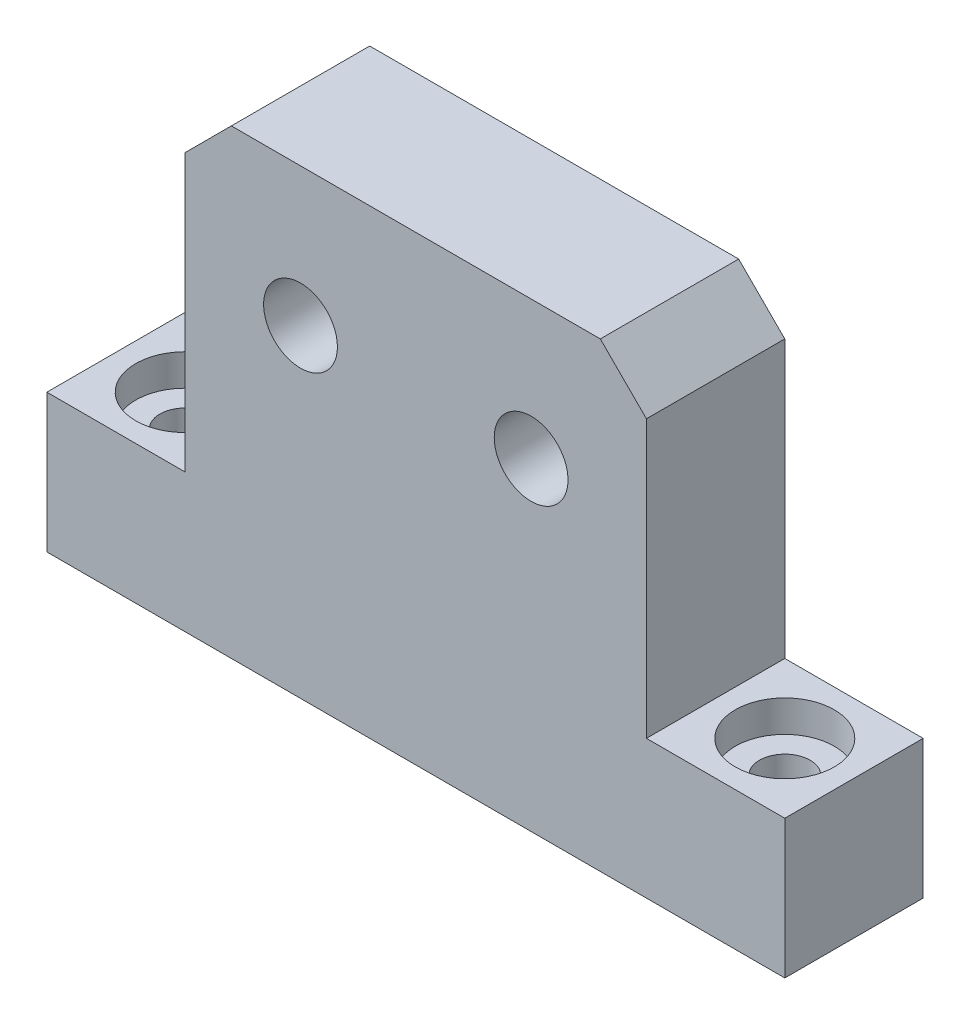
SolidWorks part; units mm, degrees
ref_plane "Front Plane" through (0, 0, 0) normal (0, 0, 1) x (1, 0, 0)
ref_plane "Top Plane" through (0, 0, 0) normal (0, 1, 0) x (1, 0, 0)
ref_plane "Right Plane" through (0, 0, 0) normal (1, 0, 0) x (0, 0, -1)
sketch "Sketch2" plane through (0, 0, 0) normal (0, 0, 1) x (1, 0, 0)
  line L0 (0, 0) -> (0, 100) construction
  line L1 (80, 0) -> (-80, 0)
  line L2 (-80, 0) -> (-80, 30)
  line L3 (-80, 30) -> (-50, 30)
  line L4 (-50, 30) -> (-50, 100)
  line L5 (-50, 100) -> (0, 100)
  line L6 (0, 70) -> (-50, 70) construction
  line L7 (-25, 100) -> (-25, 0) construction
  line L8 (25, 100) -> (25, 0) construction
  line L9 (0, 70) -> (50, 70) construction
  line L10 (50, 100) -> (0, 100)
  line L11 (50, 30) -> (50, 100)
  line L12 (80, 30) -> (50, 30)
  line L13 (80, 0) -> (80, 30)
  circle A0 centre (-25, 70) radius 8
  circle A1 centre (25, 70) radius 8
  circle A2 centre (-25, 70) radius 14 construction
  circle A3 centre (25, 70) radius 14 construction
  dimension "D5" = 16
  dimension "D7" = 28
  dimension "D1" = 100
  dimension "D2" = 80
  dimension "D3" = 30
  dimension "D4" = 30
  dimension "D6" = 70
extrude "Corpo - Furos 20mm" add sketch "Sketch2" along normal blind 30
chamfer "Chanfros 10x45°" distance 10 angle 45 2 edges at (-50, 100, 15) (50, 100, 15)
hole_wizard "Rebaixo Parafuso M10" positions "Sketch4" profile "Sketch5" counterbore size "M10" standard "ANSI Metric" end condition through all
sketch "Sketch4" plane through (0, 30, 0) normal (0, 1, 0) x (1, 0, 0)
  line L0 (-65, -15) -> (65, -15) construction
  line L2 (-50, -30) -> (-80, -30) construction
  line L3 (-80, -30) -> (-80, 0) construction
  point P0 (-65, -15)
  point P2 (65, -15)
  dimension "D1" = 15
  dimension "D2" = 15
  dimension "D3" = 130
sketch "Sketch5" plane through (-65, 30, 15) normal (1, 0, 0) x (0, 0, 1)
  line L0 (0, 0) -> (0, 30)
  line L1 (0, 30) -> (5.5, 30)
  line L3 (5.5, 30) -> (5.5, 6.85)
  line L4 (5.5, 6.85) -> (10.74, 6.85)
  line L5 (10.74, 6.85) -> (10.74, 0)
  line L7 (10.74, 0) -> (0, 0)
  line L11 (0, -6.35) -> (0, 107.95) construction
  dimension "Thru Hole Dia." = 11
  dimension "Thru Hole Depth" = 30
  dimension "C'Bore Dia." = 21.48
  dimension "C'Bore Depth" = 6.85
